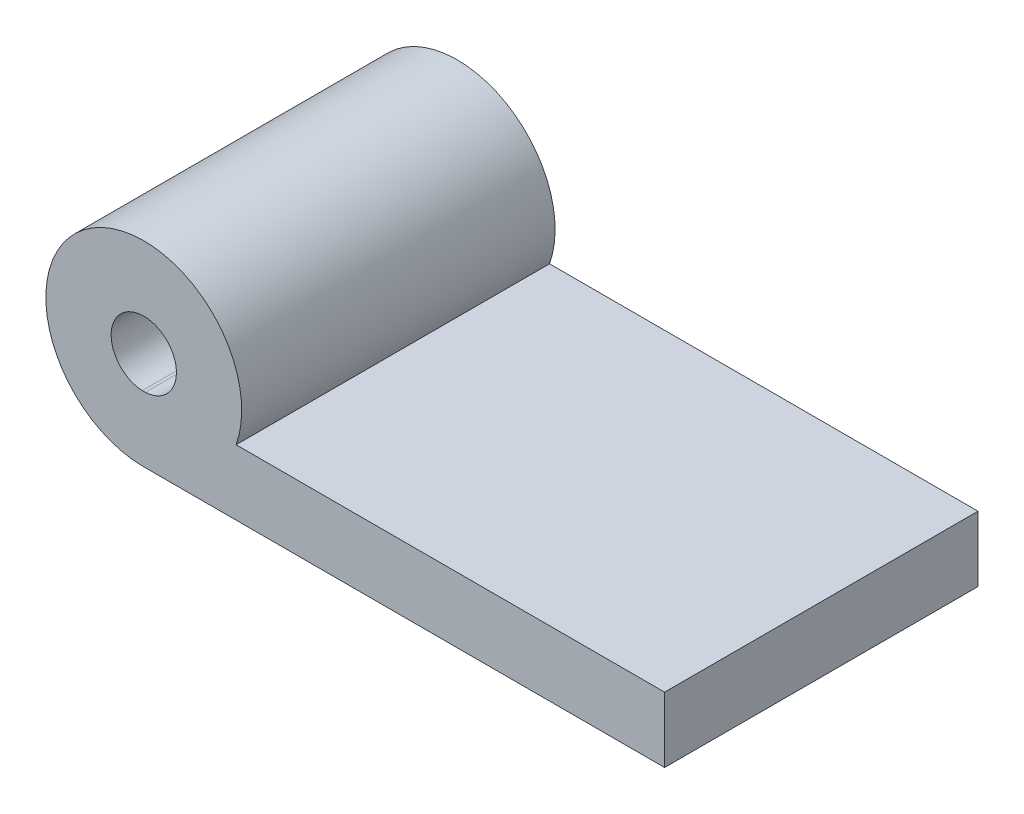
SolidWorks part; units mm, degrees
ref_plane "Front Plane" through (0, 0, 0) normal (0, 0, 1) x (1, 0, 0)
ref_plane "Top Plane" through (0, 0, 0) normal (0, 1, 0) x (1, 0, 0)
ref_plane "Right Plane" through (0, 0, 0) normal (1, 0, 0) x (0, 0, -1)
sketch "Sketch1" plane through (0, 0, 0) normal (0, 1, 0) x (1, 0, 0)
  line L1 (-45.7439, -13.8847) -> (-20.3439, -13.8847)
  line L2 (-45.7439, -13.8847) -> (-45.7439, -29.1247)
  line L3 (-45.7439, -29.1247) -> (-20.3439, -29.1247)
  line L4 (-20.3439, -13.8847) -> (-20.3439, -29.1247)
  dimension "D1" = 15.24
  dimension "D2" = 25.4
extrude "Boss-Extrude1" add sketch "Sketch1" along normal blind 3.175
sketch "Sketch3" plane through (0, 0, 29.1247) normal (0, 0, 1) x (1, 0, 0)
  circle A0 centre (-45.6705, 4.7608) radius 1.5875
  circle A1 centre (-45.6705, 4.7608) radius 4.7614
  dimension "D1" = 3.175
extrude "Boss-Extrude2" add sketch "Sketch3" against normal blind 15.24
